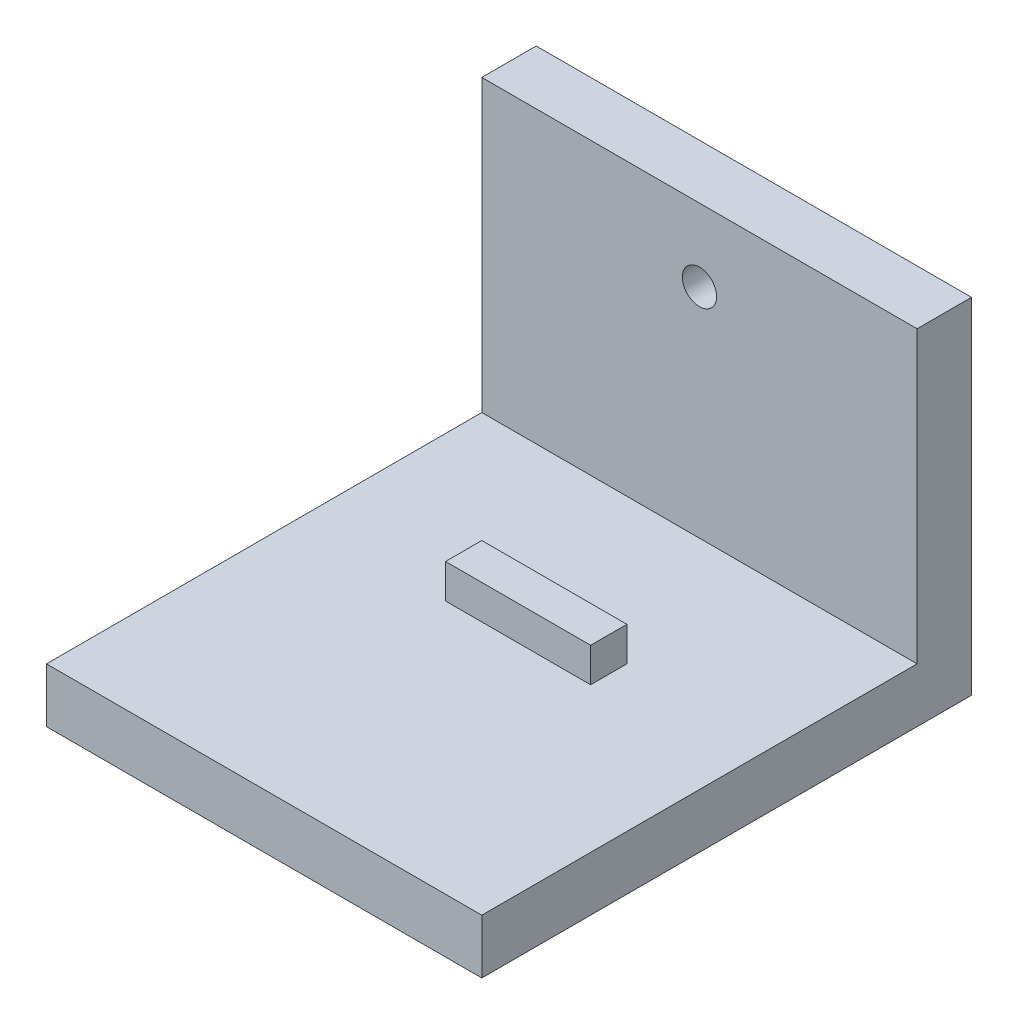
SolidWorks part; units mm, degrees
ref_plane "Front Plane" through (0, 0, 0) normal (0, 0, 1) x (1, 0, 0)
ref_plane "Top Plane" through (0, 0, 0) normal (0, 1, 0) x (1, 0, 0)
ref_plane "Right Plane" through (0, 0, 0) normal (1, 0, 0) x (0, 0, -1)
sketch "Sketch1" plane through (0, 0, 0) normal (1, 0, 0) x (0, 0, -1)
  line L0 (0, 0) -> (-42.8625, 0)
  line L1 (-42.8625, 0) -> (-42.8625, 4.7625)
  line L2 (-42.8625, 4.7625) -> (-4.7625, 4.7625)
  line L3 (-4.7625, 4.7625) -> (-4.7625, 30.1625)
  line L4 (-4.7625, 30.1625) -> (0, 30.1625)
  line L5 (0, 30.1625) -> (0, 0)
  dimension "D1" = 38.1
  dimension "D2" = 25.4
  dimension "D3" = 4.7625
extrude "Boss-Extrude1" add sketch "Sketch1" along normal blind 38.1
sketch "Sketch2" plane through (0, 4.7625, 0) normal (0, 1, 0) x (1, 0, 0)
  line L0 (38.1, -42.8625) -> (0, -42.8625) construction
  line L1 (12.7, -20.6375) -> (25.4, -20.6375)
  line L2 (12.7, -20.6375) -> (12.7, -17.4625)
  line L3 (12.7, -17.4625) -> (25.4, -17.4625)
  line L4 (25.4, -20.6375) -> (25.4, -17.4625)
  line L7 (38.1, -4.7625) -> (0, -4.7625) construction
  point P4 (19.05, -20.6375)
  point P7 (19.05, -42.8625)
  dimension "D1" = 3.175
  dimension "D2" = 12.7
  dimension "D3" = 12.7
extrude "Boss-Extrude2" add sketch "Sketch2" along normal blind 2.9972
sketch "Sketch3" plane through (0, 0, 4.7625) normal (0, 0, 1) x (1, 0, 0)
  line L0 (38.1, 30.1625) -> (0, 30.1625) construction
  line L1 (38.1, 4.7625) -> (0, 4.7625) construction
  circle A0 centre (19.05, 23.8125) radius 1.5
  point P2 (0, 0)
  point P5 (19.05, 30.1625)
  dimension "D1" = 3
  dimension "D2" = 19.05
extrude "Cut-Extrude1" cut sketch "Sketch3" against normal through all
